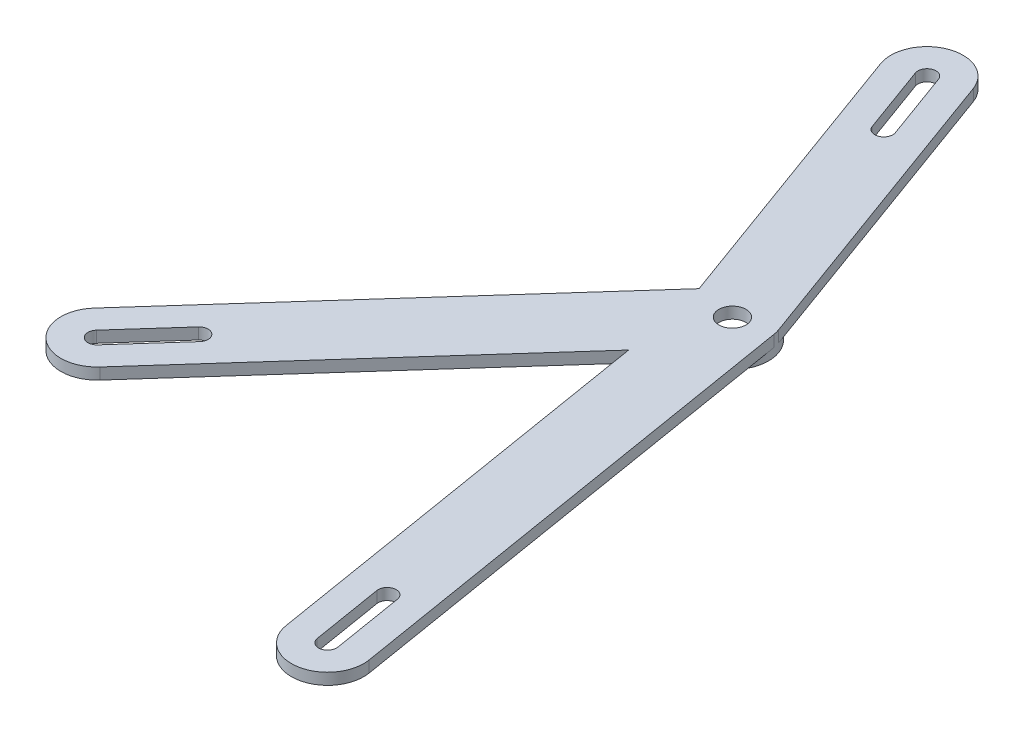
SolidWorks part; units mm, degrees
ref_plane "Front Plane" through (0, 0, 0) normal (0, 0, 1) x (1, 0, 0)
ref_plane "Top Plane" through (0, 0, 0) normal (0, 1, 0) x (1, 0, 0)
ref_plane "Right Plane" through (0, 0, 0) normal (1, 0, 0) x (0, 0, -1)
sketch "Sketch1" plane through (0, 0, 0) normal (0, 1, 0) x (1, 0, 0)
  line L1 (-55.0781, 65.6704) -> (-15.8825, -41.9018)
  line L2 (-78.9432, 56.9747) -> (-42.3518, -43.4503)
  line L6 (-42.3518, -43.4503) -> (-142.7448, -155.6549)
  line L8 (-15.283, -44.1907) -> (12.6912, -214.4599)
  line L10 (-36.0449, -74.4942) -> (-12.3728, -218.5777)
  line L11 (-36.0449, -74.4942) -> (-123.8156, -172.5914)
  arc A0 (-55.0781, 65.6704) -> (-78.9432, 56.9747) centre (-67.0106, 61.3226) ccw
  arc A3 (-142.7448, -155.6549) -> (-123.8156, -172.5914) centre (-133.2802, -164.1232) ccw
  arc A5 (-12.3728, -218.5777) -> (12.6912, -214.4599) centre (0.1592, -216.5188) ccw
  arc A6 (-15.8825, -41.9018) -> (-15.283, -44.1907) centre (-27.815, -46.2496) cw
  point P2 (-47.4128, 7.5365)
  point P10 (-27.815, -46.2496)
  point P12 (-80.5476, -105.1864)
  point P19 (-13.8279, -131.3842)
  dimension "D2" = 12.7
extrude "Boss-Extrude1" add sketch "Sketch1" along normal blind 4
sketch "Sketch3" plane through (0, 4, 0) normal (0, 1, 0) x (1, 0, 0)
  circle A0 centre (-27.815, -46.2496) radius 12.7
extrude "Boss-Extrude2" add sketch "Sketch3" against normal blind 7
sketch "Sketch5" plane through (0, 4, 0) normal (0, 1, 0) x (1, 0, 0)
  circle A0 centre (-27.815, -46.2496) radius 4.7625
  dimension "D1" = 9.525
extrude "Cut-Extrude1" cut sketch "Sketch5" against normal through all
sketch "Sketch6" plane through (0, -3, 0) normal (0, -1, 0) x (-1, 0, 0)
  circle A0 centre (27.815, -46.2496) radius 12.192
  dimension "D1" = 24.384
extrude "Cut-Extrude2" cut sketch "Sketch6" against normal blind 3
sketch "Sketch8" plane through (0, 4, 0) normal (0, 1, 0) x (1, 0, 0)
  line L0 (-27.815, -46.2496) -> (-67.0106, 61.3226) construction
  line L1 (-27.815, -46.2496) -> (0.1592, -216.5188) construction
  line L2 (-27.815, -46.2496) -> (-133.2802, -164.1232) construction
  circle A0 centre (-67.0106, 61.3226) radius 3.175
  circle A1 centre (0.1592, -216.5188) radius 3.175
  circle A2 centre (-133.2802, -164.1232) radius 3.175
  dimension "D1" = 6.35
  dimension "D2" = 6.35
  dimension "D3" = 6.35
extrude "Cut-Extrude3" cut sketch "Sketch8" against normal through all
sketch "Sketch10" plane through (0, 4, 0) normal (0, 1, 0) x (1, 0, 0)
  line L0 (-67.0106, 61.3226) -> (-48.7149, 11.11) construction
  line L1 (-67.0106, 61.3226) -> (-58.315, 37.4574) construction
  line L2 (-64.0275, 62.4095) -> (-55.3319, 38.5444)
  line L3 (-69.9938, 60.2356) -> (-61.2981, 36.3704)
  line L4 (-133.2802, -164.1232) -> (-85.2166, -110.4047) construction
  line L5 (-133.2802, -164.1232) -> (-116.3436, -145.194) construction
  line L6 (-135.6463, -162.0061) -> (-118.7098, -143.0769)
  line L7 (-130.914, -166.2402) -> (-113.9775, -147.3111)
  line L8 (0.1592, -216.5188) -> (-6.1719, -177.9836) construction
  line L9 (0.1592, -216.5188) -> (-3.9587, -191.4548) construction
  line L10 (-2.9738, -217.0335) -> (-7.0917, -191.9696)
  line L11 (3.2922, -216.0041) -> (-0.8257, -190.9401)
  arc A0 (-64.0275, 62.4095) -> (-69.9938, 60.2356) centre (-67.0106, 61.3226) ccw
  arc A1 (-61.2981, 36.3704) -> (-55.3319, 38.5444) centre (-58.315, 37.4574) ccw
  arc A2 (-135.6463, -162.0061) -> (-130.914, -166.2402) centre (-133.2802, -164.1232) ccw
  arc A3 (-113.9775, -147.3111) -> (-118.7098, -143.0769) centre (-116.3436, -145.194) ccw
  arc A4 (-2.9738, -217.0335) -> (3.2922, -216.0041) centre (0.1592, -216.5188) ccw
  arc A5 (-0.8257, -190.9401) -> (-7.0917, -191.9696) centre (-3.9587, -191.4548) ccw
  point P2 (-62.6628, 49.39)
  point P12 (-124.8119, -154.6586)
  point P21 (-1.8998, -203.9868)
  dimension "D1" = 3.175
  dimension "D3" = 3.175
  dimension "D5" = 3.175
  dimension "D2" = 25.4
  dimension "D4" = 25.4
  dimension "D6" = 25.4
extrude "Cut-Extrude4" cut sketch "Sketch10" against normal through all
